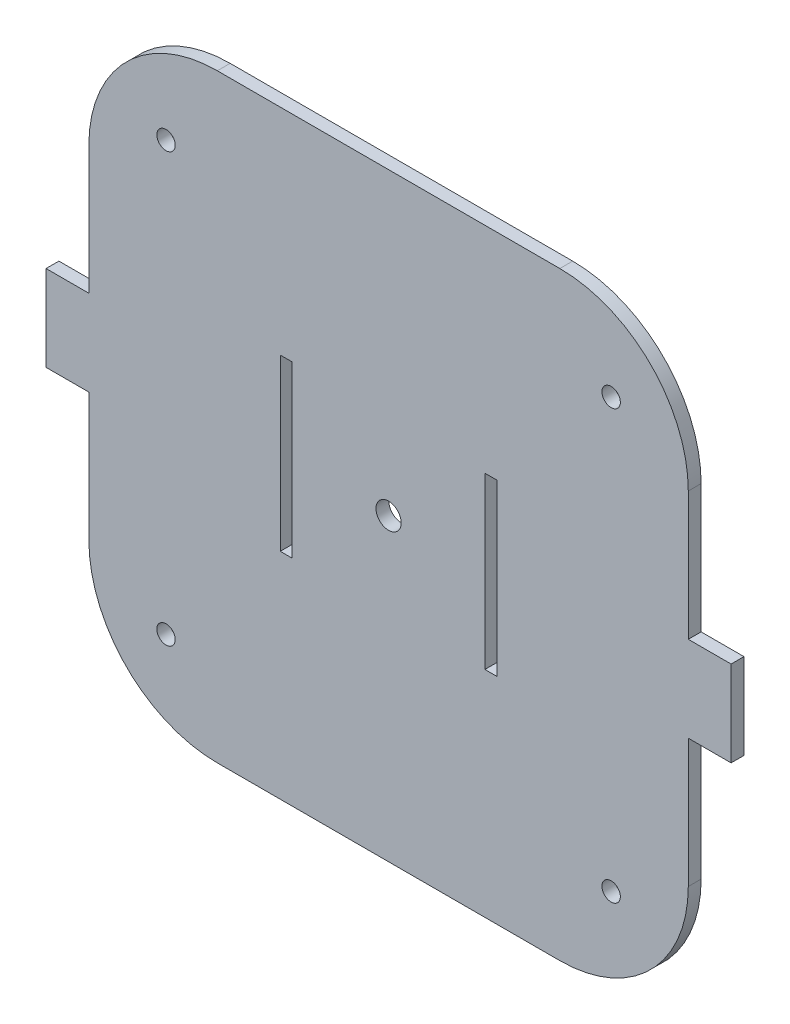
SolidWorks part; units mm, degrees
ref_plane "Alzado" through (0, 0, 0) normal (0, 0, 1) x (1, 0, 0)
ref_plane "Planta" through (0, 0, 0) normal (0, 1, 0) x (1, 0, 0)
ref_plane "Vista lateral" through (0, 0, 0) normal (1, 0, 0) x (0, 0, -1)
sketch "Croquis2" plane through (0, 0, 0) normal (0, 0, 1) x (1, 0, 0)
  line L1 (30, 110) -> (110, 110)
  line L2 (30, -30) -> (110, -30)
  line L4 (70, 110) -> (70, -30) construction
  line L5 (0, 40) -> (140, 40) construction
  line L11 (44.7, 59.85) -> (47.5, 59.85)
  line L24 (47.5, 59.85) -> (47.5, 40)
  line L25 (0, 40) -> (-10, 40) construction
  line L30 (47.5, 40) -> (47.5, 20.15)
  line L31 (47.5, 20.15) -> (44.7, 20.15)
  line L41 (140, 40) -> (150, 40) construction
  line L44 (-10, 50) -> (-10, 40)
  line L45 (-10, 40) -> (-10, 30)
  line L46 (0, 80) -> (0, 50)
  line L47 (0, 50) -> (0, 40) construction
  line L48 (150, 50) -> (150, 40)
  line L49 (150, 40) -> (150, 30)
  line L51 (0, 50) -> (-10, 50)
  line L52 (0, 30) -> (-10, 30)
  line L53 (140, 50) -> (150, 50)
  line L54 (140, 30) -> (150, 30)
  line L55 (0, 40) -> (0, 30) construction
  line L56 (0, 30) -> (0, 0)
  line L57 (140, 80) -> (140, 50)
  line L58 (140, 50) -> (140, 40) construction
  line L59 (140, 40) -> (140, 30) construction
  line L60 (140, 30) -> (140, 0)
  line L61 (44.7, 20.15) -> (44.7, 59.85)
  line L62 (92.5, 59.85) -> (92.5, 40)
  line L63 (95.3, 59.85) -> (92.5, 59.85)
  line L64 (92.5, 20.15) -> (95.3, 20.15)
  line L65 (92.5, 40) -> (92.5, 20.15)
  line L66 (95.3, 20.15) -> (95.3, 59.85)
  arc A0 (0, 80) -> (30, 110) centre (30, 80) cw
  arc A1 (0, 0) -> (30, -30) centre (30, 0) ccw
  arc A2 (110, 110) -> (140, 80) centre (110, 80) cw
  arc A28 (110, -30) -> (140, 0) centre (110, 0) ccw
  circle A29 centre (70, 40) radius 2.95
  circle A30 centre (18.0167, -10) radius 2.15
  circle A32 centre (18.0167, 90) radius 2.15
  circle A33 centre (121.9833, -10) radius 2.15
  circle A34 centre (121.9833, 90) radius 2.15
  point P17 (70, 40)
  point P18 (70, 40)
  point P37 (-17.3002, 94.761)
  dimension "D2" = 30
  dimension "D5" = 80
  dimension "D6" = 2.8
  dimension "D8" = 45
  dimension "D9" = 4.3
  dimension "D4" = 5.9
  dimension "D1" = 140
  dimension "D3" = 80
  dimension "D7" = 39.7
  dimension "D11" = 10
  dimension "D12" = 20
  dimension "D13" = 20
  dimension "D14" = 18.0167
  dimension "D16" = 50
extrude "Saliente-Extruir2" add sketch "Croquis2" along normal blind 3
